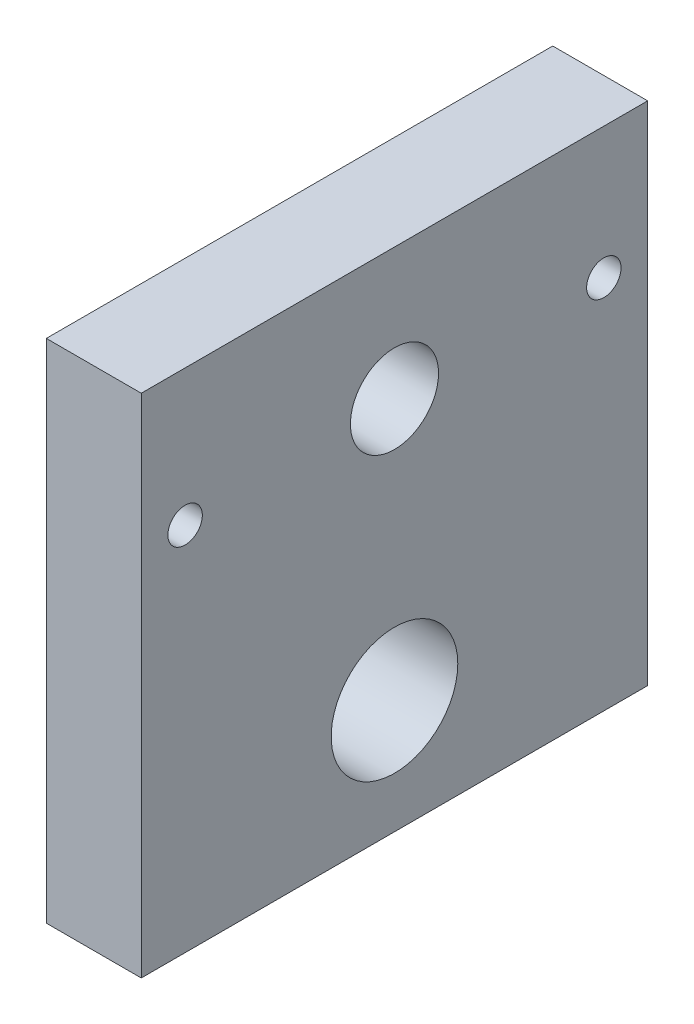
SolidWorks part; units mm, degrees
ref_plane "Front Plane" through (0, 0, 0) normal (0, 0, 1) x (1, 0, 0)
ref_plane "Top Plane" through (0, 0, 0) normal (0, 1, 0) x (1, 0, 0)
ref_plane "Right Plane" through (0, 0, 0) normal (1, 0, 0) x (0, 0, -1)
sketch "Sketch1" plane through (0, 0, 0) normal (1, 0, 0) x (0, 0, -1)
  line L1 (-25.4, -25.4) -> (25.4, -25.4)
  line L2 (-25.4, -25.4) -> (-25.4, 25.4)
  line L3 (-25.4, 25.4) -> (25.4, 25.4)
  line L4 (25.4, -25.4) -> (25.4, 25.4)
  line L5 (-25.4, -25.4) -> (25.4, 25.4) construction
  line L6 (-25.4, 25.4) -> (25.4, -25.4) construction
  point P0 (0, 0)
  dimension "D1" = 50.8
  dimension "D2" = 50.8
extrude "Boss-Extrude1" add sketch "Sketch1" along normal blind 9.525
hole_wizard "1/2 (0.5) Diameter Hole1" positions "Sketch9" profile "Sketch8" hole size "1/2" standard "ANSI Inch"
sketch "Sketch9" plane through (9.525, 0, 0) normal (1, 0, 0) x (0, 0, -1)
  line L0 (-25.4, -25.4) -> (25.4, -25.4) construction
  point P0 (0, -13.97)
  dimension "D1" = 11.43
sketch "Sketch8" plane through (9.525, -13.97, 0) normal (0, 1, 0) x (0, 0, -1)
  line L0 (0, 0) -> (0, 73.9195)
  line L1 (0, 73.9195) -> (6.35, 70.104)
  line L2 (6.35, 70.104) -> (6.35, 0)
  line L5 (6.35, 0) -> (0, 0)
  line L10 (0, 73.9195) -> (-6.35, 70.104) construction
  line L11 (0, -6.35) -> (0, 107.95) construction
  dimension "Hole Dia." = 12.7
  dimension "Hole Depth" = 70.104
  dimension "Drill Angle" = 118
hole_wizard "S (0.348) Diameter Hole1" positions "Sketch3" profile "Sketch2" hole size "S" standard "ANSI Inch"
sketch "Sketch3" plane through (9.525, 0, 0) normal (1, 0, 0) x (0, 0, -1)
  circle A0 centre (0, -13.97) radius 6.35 construction
  point P0 (0, 12.2301)
  dimension "D1" = 26.2001
  dimension "D2" = 0
sketch "Sketch2" plane through (9.525, 12.2301, 0) normal (0, 1, 0) x (0, 0, -1)
  line L0 (0, 0) -> (0, 72.7596)
  line L1 (0, 72.7596) -> (4.4196, 70.104)
  line L2 (4.4196, 70.104) -> (4.4196, 0)
  line L5 (4.4196, 0) -> (0, 0)
  line L10 (0, 72.7596) -> (-4.4196, 70.104) construction
  line L11 (0, -6.35) -> (0, 107.95) construction
  dimension "Hole Dia." = 8.8392
  dimension "Hole Depth" = 70.104
  dimension "Drill Angle" = 118
hole_wizard "#29 (0.136) Diameter Hole1" positions "Sketch5" profile "Sketch4" hole size "#29" standard "ANSI Inch"
sketch "Sketch5" plane through (9.525, 0, 0) normal (1, 0, 0) x (0, 0, -1)
  circle A0 centre (0, 12.2301) radius 4.4196 construction
  point P0 (21, 12.2301)
  point P2 (-21, 11.7415)
  dimension "D1" = 0.4886
  dimension "D2" = 0
  dimension "D3" = 21
  dimension "D4" = 42
sketch "Sketch4" plane through (9.525, 12.2301, -21) normal (0, 1, 0) x (0, 0, -1)
  line L0 (0, 0) -> (0, 71.1418)
  line L1 (0, 71.1418) -> (1.7272, 70.104)
  line L2 (1.7272, 70.104) -> (1.7272, 0)
  line L5 (1.7272, 0) -> (0, 0)
  line L10 (0, 71.1418) -> (-1.7272, 70.104) construction
  line L11 (0, -6.35) -> (0, 107.95) construction
  dimension "Hole Dia." = 3.4544
  dimension "Hole Depth" = 70.104
  dimension "Drill Angle" = 118
hole_wizard "#10-32 Tapped Hole1" positions "Sketch11" profile "Sketch10" tap size "#10-32" standard "ANSI Inch"
sketch "Sketch11" plane through (-0.6693, 7.9801, -25.4) normal (0, 0, -1) x (-1, 0, 0)
  line L0 (-10.1943, 17.4199) -> (-0.6693, 17.4199) construction
  line L2 (-10.1943, -33.3801) -> (-0.6693, -33.3801) construction
  line L3 (-10.1943, 17.4199) -> (-0.6693, 17.4199) construction
  point P0 (-5.4318, -27.0301)
  point P2 (-5.4318, 11.0699)
  point P6 (-5.4318, 17.4199)
  dimension "D1" = 0
  dimension "D2" = 0
  dimension "D3" = 6.35
  dimension "D4" = 6.35
sketch "Sketch10" plane through (4.7625, -19.05, -25.4) normal (1, 0, 0) x (0, 1, 0)
  line L0 (0, 0) -> (0, 13.1513)
  line L1 (0, 13.1513) -> (2.0193, 11.938)
  line L2 (2.0193, 11.938) -> (2.0193, 0)
  line L5 (2.0193, 0) -> (0, 0)
  line L10 (0, 13.1513) -> (-2.0193, 11.938) construction
  line L11 (0, -6.35) -> (0, 107.95) construction
  dimension "Tap Drill Dia." = 4.0386
  dimension "Tap Drill Depth" = 11.938
  dimension "Drill Angle" = 118
cosmetic thread "Hole Thread1" parameters "D1"=9.652, "D2"=4.826
cosmetic thread "Hole Thread2" parameters "D1"=9.652, "D2"=4.826
